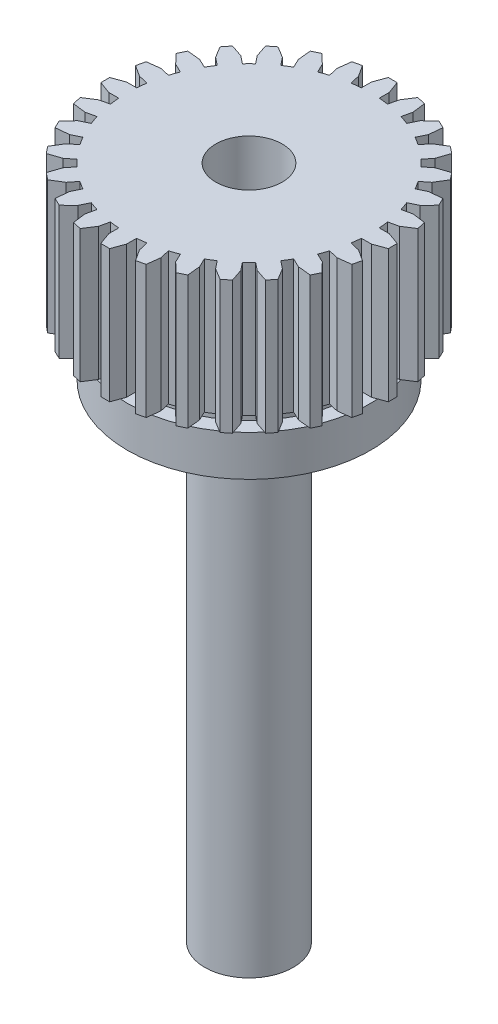
SolidWorks part; units mm, degrees
ref_plane "Plan de face" through (0, 0, 0) normal (0, 0, 1) x (1, 0, 0)
ref_plane "Plan de dessus" through (0, 0, 0) normal (0, 1, 0) x (1, 0, 0)
ref_plane "Plan de droite" through (0, 0, 0) normal (1, 0, 0) x (0, 0, -1)
ref_plane "Plan1" through (0, -2, 0) normal (0, 1, 0) x (1, 0, 0)
sketch "Esquisse1" plane through (0, -2, 0) normal (0, 1, 0) x (1, 0, 0)
  line L0 (-48.2045, -20.0151) -> (-48.5021, -20.0524)
  line L1 (-48.5021, -20.0524) -> (-48.5466, -20.2474)
  line L2 (-48.5466, -20.2474) -> (-48.2946, -20.4102)
  line L3 (-48.2946, -20.4102) -> (-48.0747, -20.4604)
  line L4 (-48.0984, -20.6705) -> (-48.324, -20.6705)
  line L5 (-48.324, -20.6705) -> (-48.6059, -20.7731)
  line L6 (-48.6059, -20.7731) -> (-48.6059, -20.9731)
  line L7 (-48.6059, -20.9731) -> (-48.324, -21.0757)
  line L8 (-48.324, -21.0757) -> (-48.0984, -21.0757)
  line L9 (-48.0747, -21.2859) -> (-48.2946, -21.3361)
  line L10 (-48.2946, -21.3361) -> (-48.5466, -21.4988)
  line L11 (-48.5466, -21.4988) -> (-48.5021, -21.6938)
  line L12 (-48.5021, -21.6938) -> (-48.2045, -21.7311)
  line L13 (-48.2045, -21.7311) -> (-47.9846, -21.6809)
  line L14 (-47.9147, -21.8805) -> (-48.1179, -21.9784)
  line L15 (-48.1179, -21.9784) -> (-48.3274, -22.1931)
  line L16 (-48.3274, -22.1931) -> (-48.2406, -22.3733)
  line L17 (-48.2406, -22.3733) -> (-47.9421, -22.3435)
  line L18 (-47.9421, -22.3435) -> (-47.7389, -22.2456)
  line L19 (-47.6264, -22.4247) -> (-47.8027, -22.5653)
  line L20 (-47.8027, -22.5653) -> (-47.9592, -22.8213)
  line L21 (-47.9592, -22.8213) -> (-47.8345, -22.9776)
  line L22 (-47.8345, -22.9776) -> (-47.5501, -22.8821)
  line L23 (-47.5501, -22.8821) -> (-47.3737, -22.7415)
  line L24 (-47.2242, -22.891) -> (-47.3648, -23.0673)
  line L25 (-47.3648, -23.0673) -> (-47.4604, -23.3517)
  line L26 (-47.4604, -23.3517) -> (-47.304, -23.4764)
  line L27 (-47.304, -23.4764) -> (-47.048, -23.32)
  line L28 (-47.048, -23.32) -> (-46.9074, -23.1436)
  line L29 (-46.7283, -23.2561) -> (-46.8262, -23.4594)
  line L30 (-46.8262, -23.4594) -> (-46.8561, -23.7579)
  line L31 (-46.8561, -23.7579) -> (-46.6759, -23.8447)
  line L32 (-46.6759, -23.8447) -> (-46.4611, -23.6352)
  line L33 (-46.4611, -23.6352) -> (-46.3633, -23.432)
  line L34 (-46.1637, -23.5018) -> (-46.2139, -23.7217)
  line L35 (-46.2139, -23.7217) -> (-46.1766, -24.0194)
  line L36 (-46.1766, -24.0194) -> (-45.9816, -24.0639)
  line L37 (-45.9816, -24.0639) -> (-45.8188, -23.8119)
  line L38 (-45.8188, -23.8119) -> (-45.7686, -23.592)
  line L39 (-45.5585, -23.6156) -> (-45.5585, -23.8412)
  line L40 (-45.5585, -23.8412) -> (-45.4559, -24.1231)
  line L41 (-45.4559, -24.1231) -> (-45.2559, -24.1231)
  line L42 (-45.2559, -24.1231) -> (-45.1533, -23.8412)
  line L43 (-45.1533, -23.8412) -> (-45.1533, -23.6156)
  line L44 (-44.9431, -23.592) -> (-44.8929, -23.8119)
  line L45 (-44.8929, -23.8119) -> (-44.7302, -24.0639)
  line L46 (-44.7302, -24.0639) -> (-44.5352, -24.0194)
  line L47 (-44.5352, -24.0194) -> (-44.4979, -23.7217)
  line L48 (-44.4979, -23.7217) -> (-44.5481, -23.5018)
  line L49 (-44.3485, -23.432) -> (-44.2506, -23.6352)
  line L50 (-44.2506, -23.6352) -> (-44.0358, -23.8447)
  line L51 (-44.0358, -23.8447) -> (-43.8557, -23.7579)
  line L52 (-43.8557, -23.7579) -> (-43.8855, -23.4594)
  line L53 (-43.8855, -23.4594) -> (-43.9834, -23.2561)
  line L54 (-43.8043, -23.1436) -> (-43.6637, -23.32)
  line L55 (-43.6637, -23.32) -> (-43.4077, -23.4764)
  line L56 (-43.4077, -23.4764) -> (-43.2513, -23.3517)
  line L57 (-43.2513, -23.3517) -> (-43.3469, -23.0673)
  line L58 (-43.3469, -23.0673) -> (-43.4875, -22.891)
  line L59 (-43.338, -22.7415) -> (-43.1616, -22.8821)
  line L60 (-43.1616, -22.8821) -> (-42.8773, -22.9776)
  line L61 (-42.8773, -22.9776) -> (-42.7526, -22.8213)
  line L62 (-42.7526, -22.8213) -> (-42.909, -22.5653)
  line L63 (-42.909, -22.5653) -> (-43.0854, -22.4247)
  line L64 (-42.9728, -22.2456) -> (-42.7696, -22.3435)
  line L65 (-42.7696, -22.3435) -> (-42.4711, -22.3733)
  line L66 (-42.4711, -22.3733) -> (-42.3843, -22.1931)
  line L67 (-42.3843, -22.1931) -> (-42.5938, -21.9784)
  line L68 (-42.5938, -21.9784) -> (-42.797, -21.8805)
  line L69 (-42.7272, -21.6809) -> (-42.5073, -21.7311)
  line L70 (-42.5073, -21.7311) -> (-42.2096, -21.6938)
  line L71 (-42.2096, -21.6938) -> (-42.1651, -21.4988)
  line L72 (-42.1651, -21.4988) -> (-42.4171, -21.3361)
  line L73 (-42.4171, -21.3361) -> (-42.637, -21.2859)
  line L74 (-42.6133, -21.0757) -> (-42.3878, -21.0757)
  line L75 (-42.3878, -21.0757) -> (-42.1059, -20.9731)
  line L76 (-42.1059, -20.9731) -> (-42.1059, -20.7731)
  line L77 (-42.1059, -20.7731) -> (-42.3878, -20.6705)
  line L78 (-42.3878, -20.6705) -> (-42.6133, -20.6705)
  line L79 (-42.637, -20.4604) -> (-42.4171, -20.4102)
  line L80 (-42.4171, -20.4102) -> (-42.1651, -20.2474)
  line L81 (-42.1651, -20.2474) -> (-42.2096, -20.0524)
  line L82 (-42.2096, -20.0524) -> (-42.5073, -20.0151)
  line L83 (-42.5073, -20.0151) -> (-42.7272, -20.0653)
  line L84 (-42.797, -19.8657) -> (-42.5938, -19.7679)
  line L85 (-42.5938, -19.7679) -> (-42.3843, -19.5531)
  line L86 (-42.3843, -19.5531) -> (-42.4711, -19.3729)
  line L87 (-42.4711, -19.3729) -> (-42.7696, -19.4028)
  line L88 (-42.7696, -19.4028) -> (-42.9728, -19.5006)
  line L89 (-43.0854, -19.3216) -> (-42.909, -19.1809)
  line L90 (-42.909, -19.1809) -> (-42.7526, -18.925)
  line L91 (-42.7526, -18.925) -> (-42.8773, -18.7686)
  line L92 (-42.8773, -18.7686) -> (-43.1616, -18.8641)
  line L93 (-43.1616, -18.8641) -> (-43.338, -19.0048)
  line L94 (-43.4875, -18.8552) -> (-43.3469, -18.6789)
  line L95 (-43.3469, -18.6789) -> (-43.2513, -18.3945)
  line L96 (-43.2513, -18.3945) -> (-43.4077, -18.2698)
  line L97 (-43.4077, -18.2698) -> (-43.6637, -18.4262)
  line L98 (-43.6637, -18.4262) -> (-43.8043, -18.6026)
  line L99 (-43.9834, -18.4901) -> (-43.8855, -18.2869)
  line L100 (-43.8855, -18.2869) -> (-43.8557, -17.9884)
  line L101 (-43.8557, -17.9884) -> (-44.0358, -17.9016)
  line L102 (-44.0358, -17.9016) -> (-44.2506, -18.1111)
  line L103 (-44.2506, -18.1111) -> (-44.3485, -18.3143)
  line L104 (-44.5481, -18.2444) -> (-44.4979, -18.0245)
  line L105 (-44.4979, -18.0245) -> (-44.5352, -17.7269)
  line L106 (-44.5352, -17.7269) -> (-44.7302, -17.6823)
  line L107 (-44.7302, -17.6823) -> (-44.8929, -17.9344)
  line L108 (-44.8929, -17.9344) -> (-44.9431, -18.1543)
  line L109 (-45.1533, -18.1306) -> (-45.1533, -17.905)
  line L110 (-45.1533, -17.905) -> (-45.2559, -17.6231)
  line L111 (-45.2559, -17.6231) -> (-45.4559, -17.6231)
  line L112 (-45.4559, -17.6231) -> (-45.5585, -17.905)
  line L113 (-45.5585, -17.905) -> (-45.5585, -18.1306)
  line L114 (-45.7686, -18.1543) -> (-45.8188, -17.9344)
  line L115 (-45.8188, -17.9344) -> (-45.9816, -17.6823)
  line L116 (-45.9816, -17.6823) -> (-46.1766, -17.7269)
  line L117 (-46.1766, -17.7269) -> (-46.2139, -18.0245)
  line L118 (-46.2139, -18.0245) -> (-46.1637, -18.2444)
  line L119 (-46.3633, -18.3143) -> (-46.4611, -18.1111)
  line L120 (-46.4611, -18.1111) -> (-46.6759, -17.9016)
  line L121 (-46.6759, -17.9016) -> (-46.8561, -17.9884)
  line L122 (-46.8561, -17.9884) -> (-46.8262, -18.2869)
  line L123 (-46.8262, -18.2869) -> (-46.7283, -18.4901)
  line L124 (-46.9074, -18.6026) -> (-47.048, -18.4262)
  line L125 (-47.048, -18.4262) -> (-47.304, -18.2698)
  line L126 (-47.304, -18.2698) -> (-47.4604, -18.3945)
  line L127 (-47.4604, -18.3945) -> (-47.3648, -18.6789)
  line L128 (-47.3648, -18.6789) -> (-47.2242, -18.8552)
  line L129 (-47.3737, -19.0048) -> (-47.5501, -18.8641)
  line L130 (-47.5501, -18.8641) -> (-47.8345, -18.7686)
  line L131 (-47.8345, -18.7686) -> (-47.9592, -18.925)
  line L132 (-47.9592, -18.925) -> (-47.8027, -19.1809)
  line L133 (-47.8027, -19.1809) -> (-47.6264, -19.3216)
  line L134 (-47.7389, -19.5006) -> (-47.9421, -19.4028)
  line L135 (-47.9421, -19.4028) -> (-48.2406, -19.3729)
  line L136 (-48.2406, -19.3729) -> (-48.3274, -19.5531)
  line L137 (-48.3274, -19.5531) -> (-48.1179, -19.7679)
  line L138 (-48.1179, -19.7679) -> (-47.9147, -19.8657)
  line L139 (-47.9846, -20.0653) -> (-48.2045, -20.0151)
  arc A0 (-48.0747, -20.4604) -> (-48.0984, -20.6705) centre (-45.3559, -20.8731) ccw
  arc A1 (-48.0984, -21.0757) -> (-48.0747, -21.2859) centre (-45.3559, -20.8731) ccw
  arc A2 (-47.9846, -21.6809) -> (-47.9147, -21.8805) centre (-45.3559, -20.8731) ccw
  arc A3 (-47.7389, -22.2456) -> (-47.6264, -22.4247) centre (-45.3559, -20.8731) ccw
  arc A4 (-47.3737, -22.7415) -> (-47.2242, -22.891) centre (-45.3559, -20.8731) ccw
  arc A5 (-46.9074, -23.1436) -> (-46.7283, -23.2561) centre (-45.3559, -20.8731) ccw
  arc A6 (-46.3633, -23.432) -> (-46.1637, -23.5018) centre (-45.3559, -20.8731) ccw
  arc A7 (-45.7686, -23.592) -> (-45.5585, -23.6156) centre (-45.3559, -20.8731) ccw
  arc A8 (-45.1533, -23.6156) -> (-44.9431, -23.592) centre (-45.3559, -20.8731) ccw
  arc A9 (-44.5481, -23.5018) -> (-44.3485, -23.432) centre (-45.3559, -20.8731) ccw
  arc A10 (-43.9834, -23.2561) -> (-43.8043, -23.1436) centre (-45.3559, -20.8731) ccw
  arc A11 (-43.4875, -22.891) -> (-43.338, -22.7415) centre (-45.3559, -20.8731) ccw
  arc A12 (-43.0854, -22.4247) -> (-42.9728, -22.2456) centre (-45.3559, -20.8731) ccw
  arc A13 (-42.797, -21.8805) -> (-42.7272, -21.6809) centre (-45.3559, -20.8731) ccw
  arc A14 (-42.637, -21.2859) -> (-42.6133, -21.0757) centre (-45.3559, -20.8731) ccw
  arc A15 (-42.6133, -20.6705) -> (-42.637, -20.4604) centre (-45.3559, -20.8731) ccw
  arc A16 (-42.7272, -20.0653) -> (-42.797, -19.8657) centre (-45.3559, -20.8731) ccw
  arc A17 (-42.9728, -19.5006) -> (-43.0854, -19.3216) centre (-45.3559, -20.8731) ccw
  arc A18 (-43.338, -19.0048) -> (-43.4875, -18.8552) centre (-45.3559, -20.8731) ccw
  arc A19 (-43.8043, -18.6026) -> (-43.9834, -18.4901) centre (-45.3559, -20.8731) ccw
  arc A20 (-44.3485, -18.3143) -> (-44.5481, -18.2444) centre (-45.3559, -20.8731) ccw
  arc A21 (-44.9431, -18.1543) -> (-45.1533, -18.1306) centre (-45.3559, -20.8731) ccw
  arc A22 (-45.5585, -18.1306) -> (-45.7686, -18.1543) centre (-45.3559, -20.8731) ccw
  arc A23 (-46.1637, -18.2444) -> (-46.3633, -18.3143) centre (-45.3559, -20.8731) ccw
  arc A24 (-46.7283, -18.4901) -> (-46.9074, -18.6026) centre (-45.3559, -20.8731) ccw
  arc A25 (-47.2242, -18.8552) -> (-47.3737, -19.0048) centre (-45.3559, -20.8731) ccw
  arc A26 (-47.6264, -19.3216) -> (-47.7389, -19.5006) centre (-45.3559, -20.8731) ccw
  arc A27 (-47.9147, -19.8657) -> (-47.9846, -20.0653) centre (-45.3559, -20.8731) ccw
extrude "Boss.-Extru.1" add sketch "Esquisse1" against normal blind 3
ref_plane "Plan2" through (0, 0, 20.8731) normal (0, 0, -1) x (-1, 0, 0)
sketch "Esquisse2" plane through (0, 0, 20.8731) normal (0, 0, -1) x (-1, 0, 0)
  line L0 (44.3559, -17.25) -> (45.3559, -17.25)
  line L1 (45.3559, -17.25) -> (45.3559, -5)
  line L2 (45.3559, -5) -> (42.9352, -5)
  line L3 (42.9352, -5) -> (42.9352, -5.3306)
  line L4 (42.9352, -5.3306) -> (42.6059, -5.3306)
  line L5 (42.6059, -5.3306) -> (42.6059, -6.25)
  line L6 (42.6059, -6.25) -> (44.3543, -6.25)
  line L7 (44.3543, -6.25) -> (44.3543, -7.25)
  line L8 (44.3543, -7.25) -> (44.3559, -7.25)
  line L9 (44.3559, -7.25) -> (44.3559, -17.25)
  line L10 (45.3559, -17.25) -> (45.3559, -5) construction
revolve "Révolution1" add sketch "Esquisse2" angle 360 about L10
hole_wizard "Diamètre du perçage Ø1.5 (1.5)1" positions "Esquisse4" profile "Esquisse3" hole size "Ø1.5" standard "Ansi Metric"
sketch "Esquisse4" plane through (0, -2, 0) normal (0, 1, 0) x (1, 0, 0)
  point P0 (-45.3559, -20.8731)
sketch "Esquisse3" plane through (-45.3559, -2, 20.8731) normal (1, 0, 0) x (0, 0, 1)
  line L0 (0, 0) -> (0, 3)
  line L1 (0, 3) -> (0.75, 3)
  line L2 (0.75, 3) -> (0.75, 0)
  line L5 (0.75, 0) -> (0, 0)
  line L10 (0, 3) -> (-0.75, 3) construction
  line L11 (0, -6.35) -> (0, 107.95) construction
  dimension "Diamètre du perçage" = 1.5
  dimension "Profondeur du perçage" = 3
  dimension "Angle de pointe" = 180
